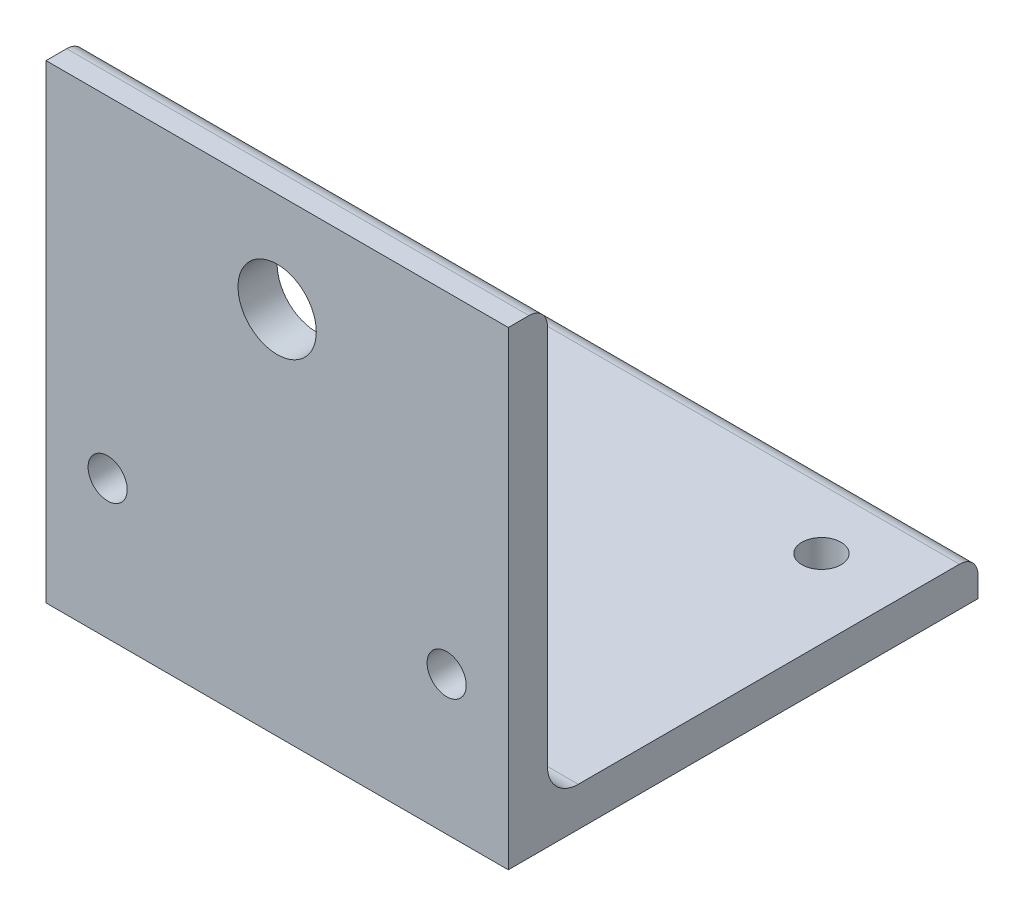
SolidWorks part; units mm, degrees
ref_plane "Front Plane" through (0, 0, 0) normal (0, 0, 1) x (1, 0, 0)
ref_plane "Top Plane" through (0, 0, 0) normal (0, 1, 0) x (1, 0, 0)
ref_plane "Right Plane" through (0, 0, 0) normal (1, 0, 0) x (0, 0, -1)
sketch "Sketch1" plane through (0, 0, 0) normal (1, 0, 0) x (0, 0, -1)
  line L0 (0, 0) -> (0, 76.2)
  line L1 (0, 76.2) -> (6.35, 76.2)
  line L2 (6.35, 76.2) -> (6.35, 6.35)
  line L3 (6.35, 6.35) -> (76.2, 6.35)
  line L4 (76.2, 6.35) -> (76.2, 0)
  line L5 (76.2, 0) -> (0, 0)
  dimension "D1" = 6.35
  dimension "D2" = 76.2
extrude "Boss-Extrude1" add sketch "Sketch1" along normal blind 75
fillet "Fillet1" radius 3 2 edges at (37.5, 6.35, -76.2) (37.5, 76.2, -6.35)
fillet "Fillet2" radius 5 1 edges at (37.5, 6.35, -6.35)
sketch "Sketch2" plane through (0, 0, 0) normal (0, 0, -1) x (-1, 0, 0)
  line L0 (0, 73.2) -> (-75, 73.2) construction
  line L2 (-75, 0) -> (0, 0) construction
  circle A0 centre (-37.5, 60) radius 6.35
  point P4 (-37.5, 73.2)
  dimension "D2" = 12.7
  dimension "D1" = 60
extrude "Cut-Extrude1" cut sketch "Sketch2" along normal through all contours A0
sketch "Sketch3" plane through (0, 0, 0) normal (0, 0, 1) x (1, 0, 0)
  line L0 (0, 22.5) -> (10, 22.5) construction
  line L1 (0, 76.2) -> (0, 0) construction
  line L2 (10, 22.5) -> (65, 22.5) construction
  line L3 (65, 22.5) -> (75, 22.5) construction
  line L4 (75, 76.2) -> (75, 0) construction
  line L5 (75, 0) -> (0, 0) construction
  circle A0 centre (10, 22.5) radius 3.175
  circle A1 centre (65, 22.5) radius 3.175
  dimension "D1" = 6.35
  dimension "D2" = 22.5
  dimension "D3" = 10
extrude "Cut-Extrude2" cut sketch "Sketch3" against normal through all
sketch "Sketch4" plane through (0, 0, 0) normal (0, -1, 0) x (1, 0, 0)
  line L0 (0, -63.5) -> (12.7, -63.5) construction
  line L1 (0, 0) -> (0, -76.2) construction
  line L2 (12.7, -63.5) -> (62.3, -63.5) construction
  line L3 (62.3, -63.5) -> (75, -63.5) construction
  line L4 (75, 0) -> (75, -76.2) construction
  line L5 (75, -76.2) -> (0, -76.2) construction
  circle A0 centre (12.7, -63.5) radius 3.175
  circle A1 centre (62.3, -63.5) radius 3.175
  dimension "D2" = 6.35
  dimension "D1" = 12.7
  dimension "D3" = 12.7
extrude "Cut-Extrude3" cut sketch "Sketch4" against normal through all
